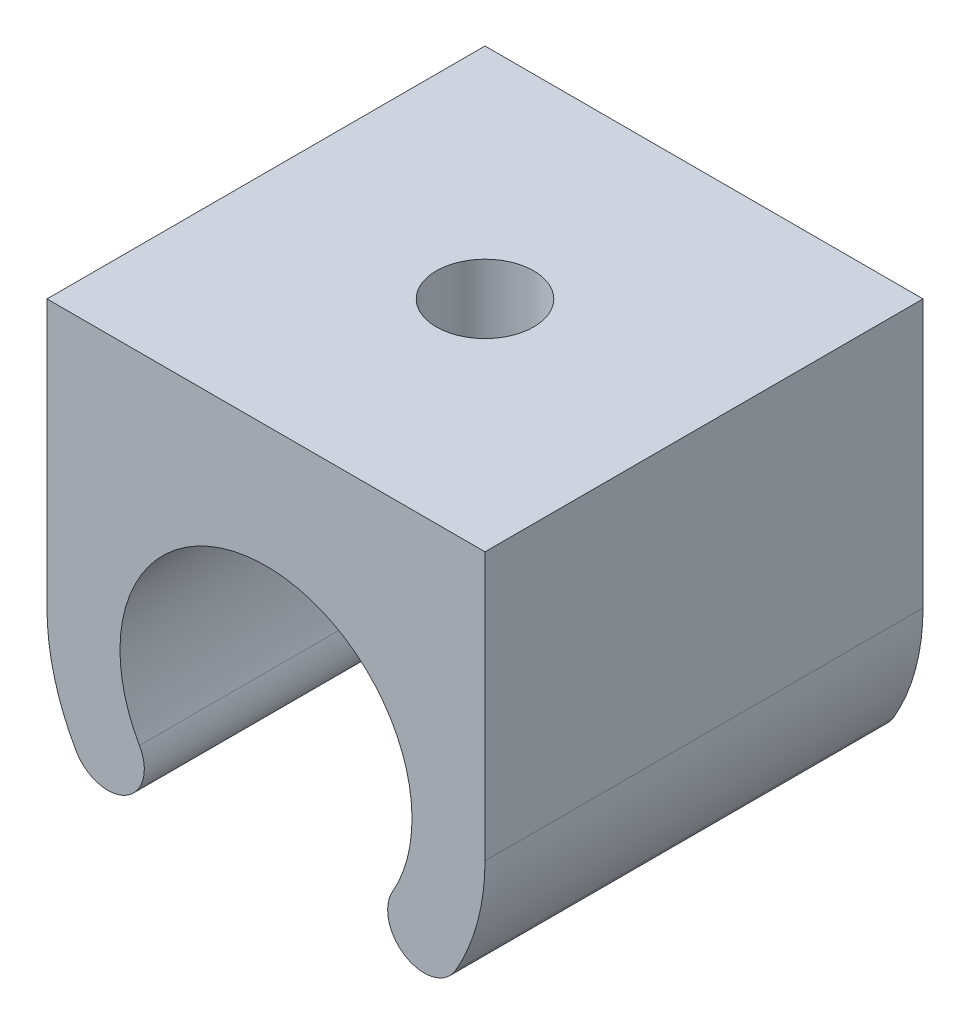
SolidWorks part; units mm, degrees
ref_plane "Ebene vorne" through (0, 0, 0) normal (0, 0, 1) x (1, 0, 0)
ref_plane "Ebene oben" through (0, 0, 0) normal (0, 1, 0) x (1, 0, 0)
ref_plane "Ebene rechts" through (0, 0, 0) normal (1, 0, 0) x (0, 0, -1)
sketch "Skizze1" plane through (0, 0, 0) normal (0, 0, 1) x (1, 0, 0)
  line L0 (-4.5, 5.5) -> (4.5, 5.5)
  line L1 (4.5, 5.5) -> (4.5, 0)
  line L2 (-4.5, 0) -> (-4.5, 5.5)
  arc A0 (2.6, -1.4967) -> (-2.6, -1.4967) centre (0, 0) ccw
  arc A1 (4.5, 0) -> (3.9, -2.245) centre (0, 0) cw
  arc A2 (-3.9, -2.245) -> (-2.6, -1.4967) centre (-3.25, -1.8708) ccw
  arc A3 (2.6, -1.4967) -> (3.9, -2.245) centre (3.25, -1.8708) ccw
  arc A4 (-3.9, -2.245) -> (-4.5, 0) centre (0, 0) cw
  point P11 (1.5584, -2.9553)
  dimension "D1" = 6
  dimension "D3" = 2.5
  dimension "D4" = 5
  dimension "D2" = 1.5
extrude "Aufsatz-Linear austragen1" add sketch "Skizze1" along normal mid plane 9
sketch "Skizze3" plane through (0, 5.5, 0) normal (0, 1, 0) x (1, 0, 0)
  circle A0 centre (0, 0) radius 1
  dimension "D1" = 2
extrude "Schnitt-Linear austragen1" cut sketch "Skizze3" against normal up to next
